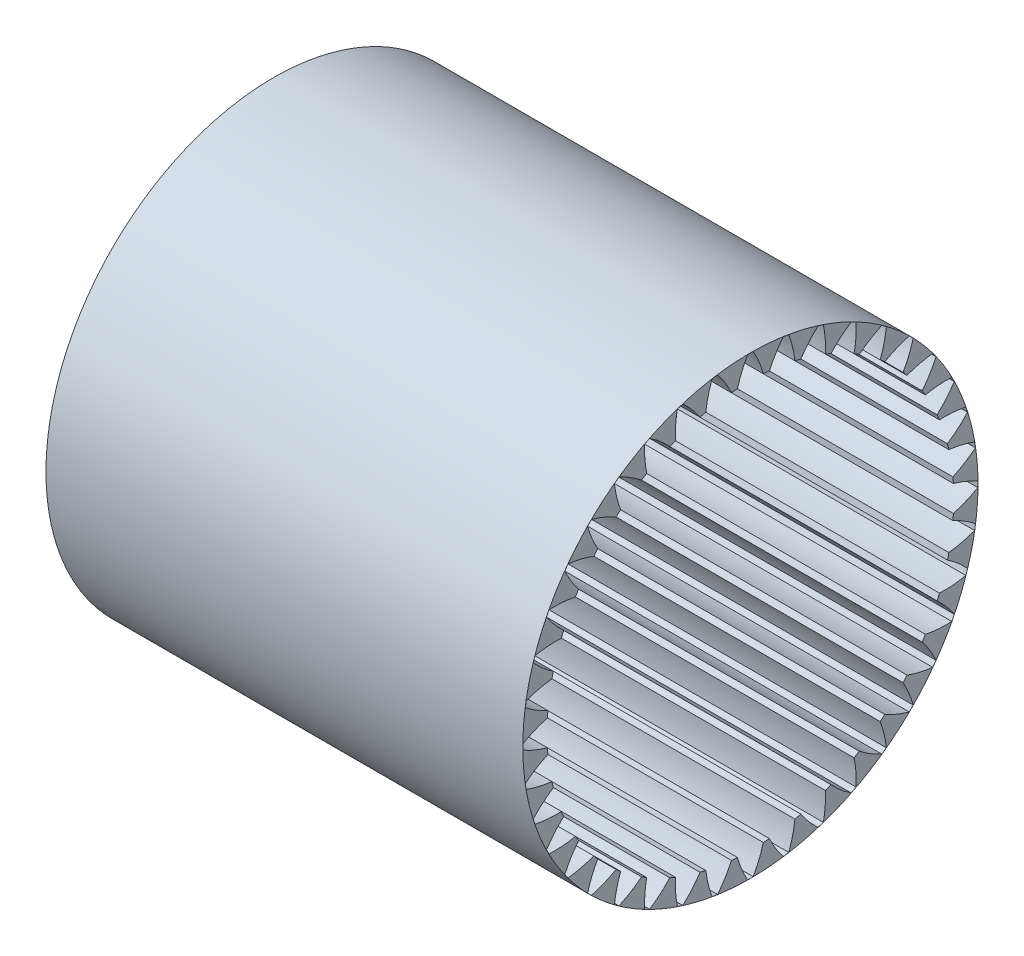
SolidWorks part; units mm, degrees
ref_plane "Plane1" through (0, 0, 0) normal (0, 0, 1) x (1, 0, 0)
ref_plane "Plane2" through (0, 0, 0) normal (0, 1, 0) x (1, 0, 0)
ref_plane "Plane3" through (0, 0, 0) normal (1, 0, 0) x (0, 0, -1)
sketch "HoldingSke" plane through (0, 0, 0) normal (0, 1, 0) x (1, 0, 0)
  line L0 (0, 0) -> (0.383, -0.3214)
  line L1 (-15, 0) -> (100, 0) construction
  line L2 (0, 0) -> (-2.1039, 2.3779)
  line L3 (0, 0) -> (-11.863, 4.5341)
  line L4 (0, 0) -> (6.6156, 5.5511)
  line L5 (0, 0) -> (-23.7986, -8.8762)
  line L6 (0, 0) -> (-10.5278, -7.1032)
  line L7 (-2.1039, 2.3779) -> (3.3635, 27.1825)
  line L8 (-76.2, 4.3779) -> (-54.61, 4.3779)
  line L9 (-71.009, 38.7566) -> (-53.1078, 45.2721)
  line L10 (-76.2, 71.12) -> (104.1128, 71.12)
  line L11 (0, 0) -> (-12, 0)
  line L12 (-76.2, 101.6) -> (-76.133, 101.6)
  line L13 (24.9733, 27.94) -> (52.9518, 28.4284)
  line L14 (24.9733, 27.94) -> (24.9743, 27.94)
  line L15 (24.9733, 27.94) -> (100.4006, 29.5858)
  circle A0 centre (0, 0) radius 12.5
  circle A1 centre (0, 0) radius 12.7
  circle A2 centre (0, 0) radius 12.7
  dimension "MHD" = 25.4
  dimension "Hub_dia" = 25.4
  dimension "Diameter" = 25
  dimension "Num_teeth" = 40
  dimension "Pitch" = 0.5
  dimension "Overall_len" = 25.4
  dimension "Show_teeth" = 40
  dimension "Thickness" = 12.7
  dimension "OAL" = 25.4001
  dimension "T_dim" = 21.59
  dimension "Ap" = 20
  dimension "H" = 19.05
  dimension "Pitch_radius" = 180.3128
  dimension "Width" = 12
  dimension "Backlash" = 0.067
  dimension "Addendum_fac" = 1
  dimension "Dedendum_fac" = 1.25
  dimension "Clearance_fac" = 0.25
  dimension "Dedendum_add" = 0.001
  dimension "Module" = 2
sketch "BasProSke" plane through (0, 0, 0) normal (0, 1, 0) x (1, 0, 0)
  line L0 (-10, 0) -> (60, 0) construction
  line L1 (0, 38) -> (0, 42.5264)
  line L2 (0, 38) -> (89.0937, 38)
  line L3 (89.0937, 38) -> (89.0937, 42.5264)
  line L4 (89.0937, 42.5264) -> (0, 42.5264)
  dimension "Thickness" = 89.0937
  dimension "Diameter" = 85.0528
  dimension "Inside_diameter" = 76
revolve "Base-Revolve" add sketch "BasProSke" angle 360 about L0
sketch "TooCutSke" plane through (0, 0, 0) normal (1, 0, 0) x (0, 0, -1)
  line L3 (1.7379, 39.9622) -> (1.7379, 53.6633) construction
  line L4 (0, 0) -> (0, 59.563) construction
  line L5 (0, 0) -> (-5.3609, 68.1169) construction
  line L6 (-16.8604, 32.6066) -> (35.072, 36.6938) construction
  circle A0 centre (0, 0) radius 40 construction
  circle A1 centre (0, 0) radius 42.501 construction
  circle A2 centre (0, 0) radius 33.8289 construction
  circle A3 centre (0, 0) radius 37.9746 construction
  arc A4 (2.4273, 37.8969) -> (0.5225, 42.4978) centre (-16.8604, 32.6066) ccw
  arc A5 (2.4273, 37.8969) -> (-2.4273, 37.8969) centre (0, 0) ccw
  arc A6 (0.5225, 42.4978) -> (-0.5225, 42.4978) centre (0, 0) ccw
  arc A7 (-0.5225, 42.4978) -> (-2.4273, 37.8969) centre (16.8604, 32.6066) ccw
  dimension "Pitch_dia" = 80
  dimension "Base_dia" = 67.6579
  dimension "Root_dia" = 85.002
  dimension "Overcut_dia" = 75.9492
  dimension "Flank_rad" = 20
  dimension "Half_ang" = 4.5
  dimension "Half_CT" = 1.7379
extrude "ToothCut" cut sketch "TooCutSke" along normal through all
fillet "Breaks" [suppressed] radius 0.2
fillet "RootFillets" [suppressed] radius 0.501
pattern_circular "TeethCuts" count 40 every 9 about axis through (-10, 0, 0) along (1, 0, 0) of "RootFillets", "Breaks", "ToothCut"
scale "Scale1" scale about centroid uniform scaling yes scale factor 0.399752
equation "' \"Module@HoldingSke\" = 6.35"
equation "' \"Num_teeth@HoldingSke\" = 24"
equation "' \"Ap@HoldingSke\" =  14.5"
equation "' \"Ap@HoldingSke\" = 14.5"
equation "' \"Width@HoldingSke\" = 12"
equation "' \"Diameter@HoldingSke\" = 8 * 25.4"
equation "' \"Show_teeth@HoldingSke\" = 100"
equation "' \"Backlash@HoldingSke\" = 0.009 * 25.4"
equation "' \"Addendum_fac@HoldingSke\" = 1.0"
equation "' \"Dedendum_fac@HoldingSke\" = 1.25"
equation "' \"Dedendum_add@HoldingSke\" = 0.00005 * 25.4"
equation "' \"Clearance_fac@HoldingSke\" = 0.25"
equation "\"Pitch@HoldingSke\" = 1 / \"Module@HoldingSke\" "
equation "\"Overcut_dia@TooCutSke\" = (\"Num_teeth@HoldingSke\" - 2 * \"Addendum_fac@HoldingSke\") / \"Pitch@HoldingSke\" - 0.002 * 25.4"
equation "\"Pitch_dia@TooCutSke\" = \"Num_teeth@HoldingSke\" / \"Pitch@HoldingSke\""
equation "\"Base_dia@TooCutSke\" = \"Num_teeth@HoldingSke\" / \"Pitch@HoldingSke\" * cos((\"Ap@HoldingSke\"  * 3.14159265 / 180)) * 0.90"
equation "\"Root_dia@TooCutSke\" = \"Num_teeth@HoldingSke\"  / \"Pitch@HoldingSke\" + 2 *  \"Dedendum_fac@HoldingSke\"/ \"Pitch@HoldingSke\" + \"Dedendum_add@HoldingSke\" * 2"
equation "\"Half_ang@TooCutSke\" = 180 / \"Num_teeth@HoldingSke\""
equation "\"Half_CT@TooCutSke\" = \"Num_teeth@HoldingSke\" / \"Pitch@HoldingSke\" * sin((3.14159265 / 2 / \"Num_teeth@HoldingSke\")) / 2 + 10 * \"Backlash@HoldingSke\" / 4"
equation "\"Flank_rad@TooCutSke\" = \"Num_teeth@HoldingSke\" / \"Pitch@HoldingSke\" / 4"
equation "\"Radius@RootFillets\"= \"Clearance_fac@HoldingSke\" / \"Pitch@HoldingSke\" + \"Dedendum_add@HoldingSke\""
equation "\"Break_rad@Breaks\" = 0.02 / \"Pitch@HoldingSke\" * 5"
equation "\"Num_teeth@TeethCuts\" = int( \"Show_teeth@HoldingSke\" ) + 1"
equation "\"Num_teeth@TeethCuts\" = ((sgn( \"Num_teeth@TeethCuts\" - \"Num_teeth@HoldingSke\" )-1)*( \"Num_teeth@TeethCuts\" - \"Num_teeth@HoldingSke\" ))/-2+ \"Num_teeth@HoldingSke\""
equation "\"Num_teeth@TeethCuts\" = ((sgn( \"Num_teeth@TeethCuts\" - 2.0)+1)*( \"Num_teeth@TeethCuts\" - 2.0))/2 +2.0"
equation "\"Angle@TeethCuts\" = 360.0 / \"Num_teeth@HoldingSke\""
equation "\"Diameter@BasProSke\" = \"Num_teeth@HoldingSke\"  / \"Pitch@HoldingSke\" + 2 *  \"Dedendum_fac@HoldingSke\"/ \"Pitch@HoldingSke\" + \"Dedendum_add@HoldingSke\" * 2 + 0.002 * 25.4"
equation "\"Diameter@BasProSke\" = ((sgn( \"Diameter@BasProSke\"  - \"Diameter@HoldingSke\" )+1)*( \"Diameter@BasProSke\"  - \"Diameter@HoldingSke\" ))/2 + \"Diameter@HoldingSke\""
equation "\"Inside_diameter@BasProSke\" =  (\"Num_teeth@HoldingSke\" - 2 * \"Addendum_fac@HoldingSke\") / \"Pitch@HoldingSke\" "
equation "\"Thickness@BasProSke\"=35.6153564*85.0528/34"
